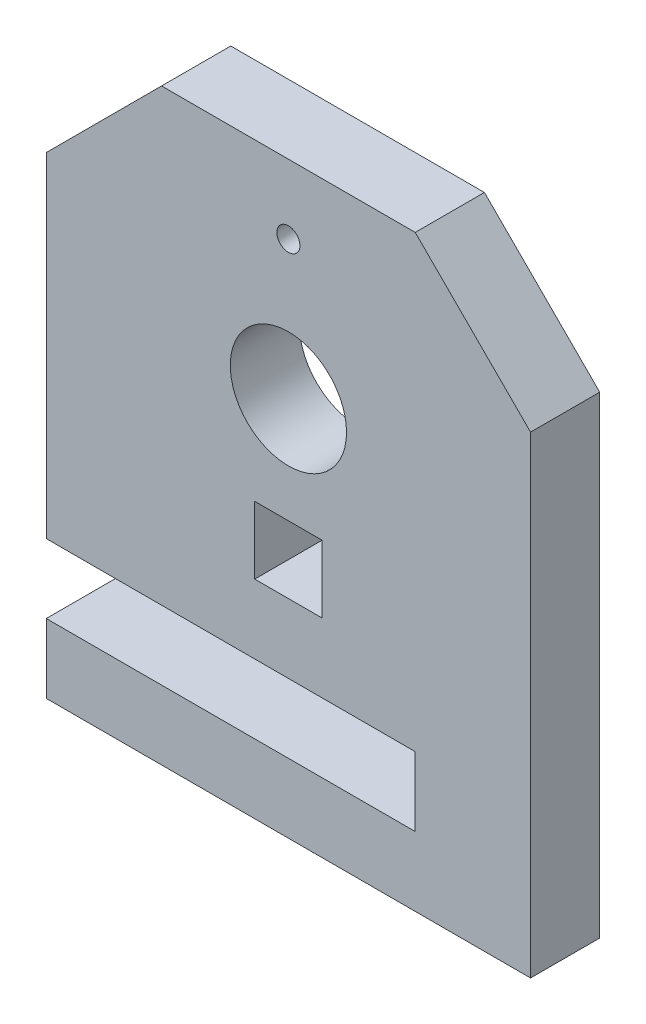
SolidWorks part; units mm, degrees
ref_plane "Front Plane" through (0, 0, 0) normal (0, 0, 1) x (1, 0, 0)
ref_plane "Top Plane" through (0, 0, 0) normal (0, 1, 0) x (1, 0, 0)
ref_plane "Right Plane" through (0, 0, 0) normal (1, 0, 0) x (0, 0, -1)
sketch "Sketch1" plane through (0, 0, 0) normal (0, 0, 1) x (1, 0, 0)
  line L0 (8.5483, 11.7097) -> (13.5483, 6.7097)
  line L1 (-7.4517, 11.7097) -> (13.5483, 11.7097)
  line L2 (-7.4517, 11.7097) -> (-7.4517, -7.7903)
  line L3 (-7.4517, -13.7903) -> (13.5483, -13.7903)
  line L4 (13.5483, 11.7097) -> (13.5483, -13.7903)
  line L5 (3.0483, 11.7097) -> (3.0483, 6.905) construction
  line L6 (-2.4517, 11.7097) -> (-7.4517, 6.7097)
  line L7 (-7.4517, -10.7903) -> (8.5483, -10.7903)
  line L8 (1.5883, -1.8703) -> (4.5083, -1.8703)
  line L9 (1.5883, -1.8703) -> (1.5883, -4.7903)
  line L10 (1.5883, -4.7903) -> (4.5083, -4.7903)
  line L11 (4.5083, -1.8703) -> (4.5083, -4.7903)
  line L12 (8.5483, -10.7903) -> (8.5483, -7.7903)
  line L13 (8.5483, -7.7903) -> (-7.4517, -7.7903)
  line L14 (-7.4517, -10.7903) -> (-7.4517, -13.7903)
  circle A0 centre (3.0483, 2.7097) radius 2.52
  circle A1 centre (3.0483, 8.7097) radius 0.5
  point P16 (3.0483, -1.8703)
  dimension "D5" = 5.04
  dimension "D6" = 16.5
  dimension "D11" = 1
  dimension "D12" = 6
  dimension "D1" = 25.5
  dimension "D2" = 21
  dimension "D3" = 5
  dimension "D4" = 5
  dimension "D7" = 2.92
  dimension "D8" = 2.92
  dimension "D9" = 9
  dimension "D10" = 10.5
  dimension "D13" = 3
  dimension "D14" = 16
  dimension "D15" = 3
  dimension "D16" = 5
  dimension "D17" = 3
extrude "Boss-Extrude1" add sketch "Sketch1" along normal blind 3
